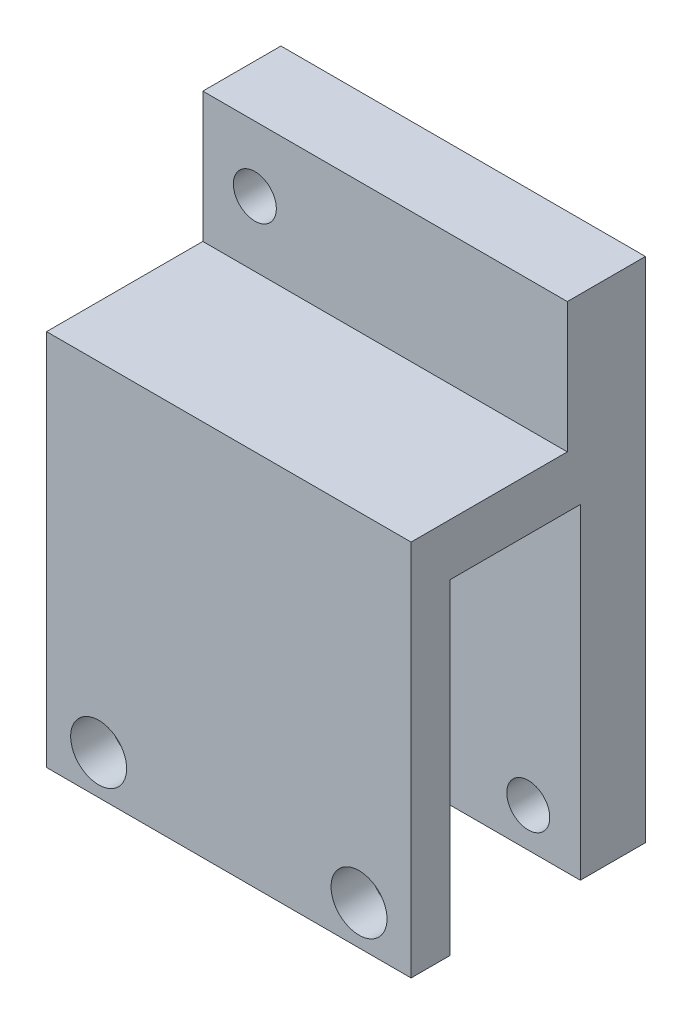
SolidWorks part; units mm, degrees
material "1060 合金"
ref_plane "前视基准面" through (0, 0, 0) normal (0, 0, 1) x (1, 0, 0)
ref_plane "上视基准面" through (0, 0, 0) normal (0, 1, 0) x (1, 0, 0)
ref_plane "右视基准面" through (0, 0, 0) normal (1, 0, 0) x (0, 0, -1)
sketch "草图2" plane through (0, 0, 0) normal (1, 0, 0) x (0, 0, -1)
  line L0 (-15, 0) -> (-18, 0)
  line L1 (0, 0) -> (-5, 0)
  line L2 (0, 0) -> (0, 39)
  line L3 (0, 39) -> (-6, 39)
  line L4 (-18, 0) -> (-18, 29)
  line L7 (-18, 29) -> (-6, 29)
  line L8 (-6, 39) -> (-6, 29)
  line L10 (-15, 0) -> (-15, 25)
  line L11 (-15, 25) -> (-5, 25)
  line L12 (-5, 0) -> (-5, 25)
  dimension "D1" = 10
  dimension "D2" = 3
  dimension "D3" = 5
  dimension "D4" = 25
  dimension "D5" = 4
  dimension "D6" = 6
  dimension "D7" = 10
extrude "凸台-拉伸1" add sketch "草图2" along normal mid plane 28
hole_wizard "M4 螺纹孔1" positions "草图4" profile "草图3" tap size "M4" standard "GB" end condition up to next
sketch "草图4" plane through (0, 0, 6) normal (0, 0, 1) x (1, 0, 0)
  line L0 (14, 39) -> (14, 29) construction
  line L1 (14, 39) -> (-14, 39) construction
  point P0 (-10, 34)
  dimension "D1" = 24
  dimension "D2" = 5
sketch "草图3" plane through (-10, 34, 6) normal (1, 0, 0) x (0, -1, 0)
  line L0 (0, 0) -> (0, 6)
  line L1 (0, 6) -> (1.65, 6)
  line L2 (1.65, 6) -> (1.65, 0)
  line L5 (1.65, 0) -> (0, 0)
  line L11 (0, -6.35) -> (0, 107.95) construction
  dimension "通孔螺纹孔钻头直径" = 3.3
  dimension "通孔螺纹孔钻头深度" = 6
cosmetic thread "孔螺蚊线1" parameters "D2"=4
hole_wizard "M4 螺纹孔2" positions "草图6" profile "草图5" tap size "M4" standard "GB"
sketch "草图6" plane through (0, 0, 0) normal (0, 0, -1) x (-1, 0, 0)
  line L0 (-14, 25) -> (14, 25) construction
  line L1 (14, 0) -> (14, 39) construction
  line L2 (-14, 0) -> (-14, 39) construction
  point P0 (10, 3)
  point P2 (-10, 3)
  dimension "D1" = 22
  dimension "D2" = 4
  dimension "D3" = 4
sketch "草图5" plane through (-10, 3, 0) normal (1, 0, 0) x (0, 1, 0)
  line L0 (0, 0) -> (0, 5)
  line L1 (0, 5) -> (1.65, 5)
  line L2 (1.65, 5) -> (1.65, 0)
  line L5 (1.65, 0) -> (0, 0)
  line L11 (0, -6.35) -> (0, 107.95) construction
  dimension "通孔螺纹孔钻头直径" = 3.3
  dimension "通孔螺纹孔钻头深度" = 5
cosmetic thread "孔螺蚊线2" parameters "D2"=4
cosmetic thread "孔螺蚊线3" parameters "D2"=4
hole_wizard "M4 间隙孔1" positions "草图8" profile "草图7" hole size "M4" standard "GB"
sketch "草图8" plane through (0, 0, 18) normal (0, 0, 1) x (1, 0, 0)
  circle A0 centre (10, 3) radius 1.65 construction
  point P0 (-10, 3)
  point P3 (10, 3)
sketch "草图7" plane through (-10, 3, 18) normal (1, 0, 0) x (0, -1, 0)
  line L0 (0, 0) -> (0, 3)
  line L1 (0, 3) -> (2.15, 3)
  line L2 (2.15, 3) -> (2.15, 0)
  line L5 (2.15, 0) -> (0, 0)
  line L11 (0, -6.35) -> (0, 107.95) construction
  dimension "通孔孔直径" = 4.3
  dimension "通孔孔深度" = 3
